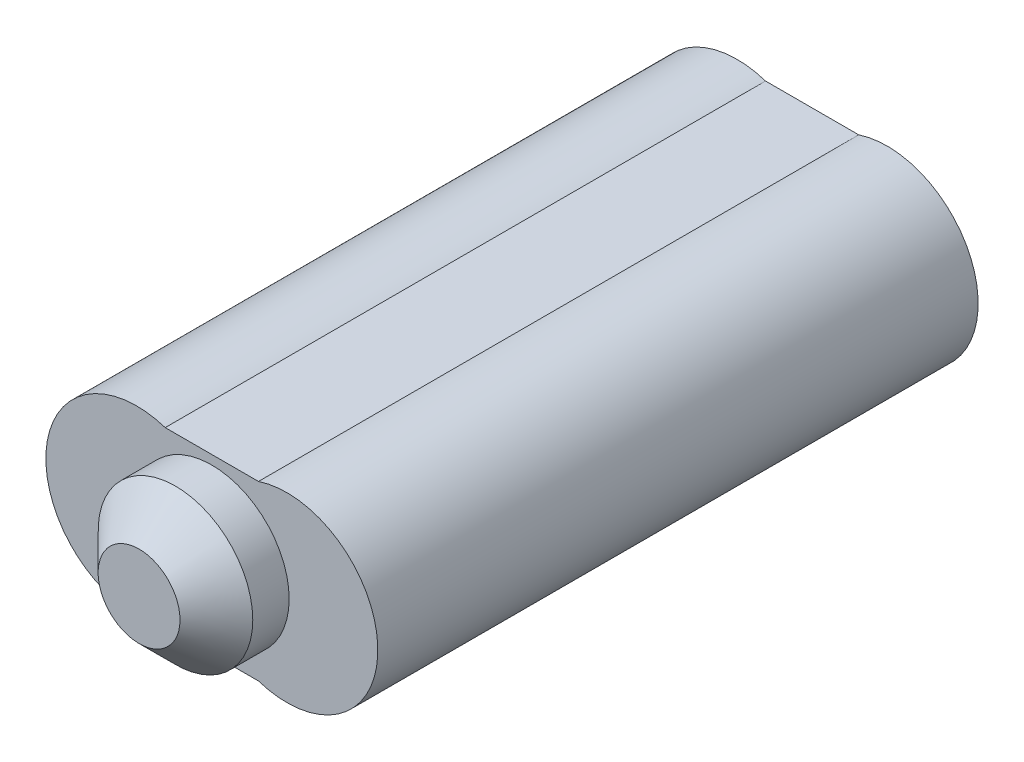
SolidWorks part; units mm, degrees
ref_plane "Front Plane" through (0, 0, 0) normal (0, 0, 1) x (1, 0, 0)
ref_plane "Top Plane" through (0, 0, 0) normal (0, 1, 0) x (1, 0, 0)
ref_plane "Right Plane" through (0, 0, 0) normal (1, 0, 0) x (0, 0, -1)
sketch "Sketch1" plane through (0, 0, 0) normal (0, 0, 1) x (1, 0, 0)
  line L0 (0, 0) -> (16.5, 0) construction
  line L1 (3.1225, 9.5) -> (13.3775, 9.5)
  line L2 (3.1225, -9.5) -> (13.3775, -9.5)
  arc A0 (3.1225, 9.5) -> (3.1225, -9.5) centre (0, 0) ccw
  arc A1 (13.3775, -9.5) -> (13.3775, 9.5) centre (16.5, 0) ccw
  arc A2 (10, 0) -> (3.1225, 9.5) centre (0, 0) ccw construction
  arc A3 (3.1225, -9.5) -> (10, 0) centre (0, 0) ccw construction
  arc A4 (6.5, 0) -> (13.3775, -9.5) centre (16.5, 0) ccw construction
  arc A5 (13.3775, 9.5) -> (6.5, 0) centre (16.5, 0) ccw construction
  dimension "D2" = 20
  dimension "D1" = 19
  dimension "D3" = 16.5
extrude "Boss-Extrude1" add sketch "Sketch1" along normal blind 66
sketch "Sketch2" plane through (0, 0, 66) normal (0, 0, 1) x (1, 0, 0)
  line L0 (-10, 0) -> (26.5, 0) construction
  arc A0 (3.1225, 9.5) -> (3.1225, -9.5) centre (0, 0) ccw construction
  arc A1 (13.3775, -9.5) -> (13.3775, 9.5) centre (16.5, 0) ccw construction
  circle A2 centre (8.25, 0) radius 8.5
  dimension "D1" = 17
extrude "Boss-Extrude2" add sketch "Sketch2" along normal blind 8
chamfer "Chamfer1" distance 4 angle 45 1 edges at (16.75, 0, 74)
